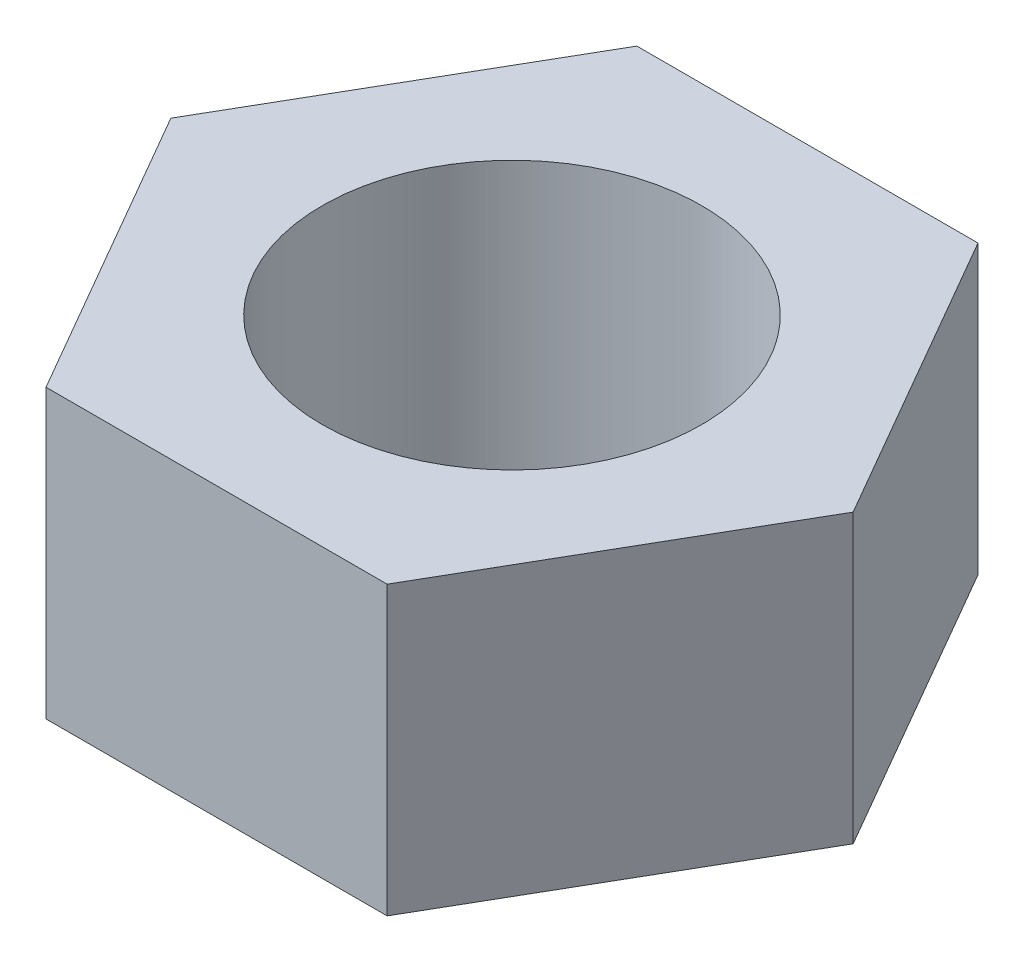
SolidWorks part; units mm, degrees
ref_plane "Front Plane" through (0, 0, 0) normal (0, 0, 1) x (1, 0, 0)
ref_plane "Top Plane" through (0, 0, 0) normal (0, 1, 0) x (1, 0, 0)
ref_plane "Right Plane" through (0, 0, 0) normal (1, 0, 0) x (0, 0, -1)
sketch "Sketch1" plane through (0, 0, 0) normal (0, 1, 0) x (1, 0, 0)
  line L1 (3.1466, -5.45) -> (6.2931, 0)
  line L2 (6.2931, 0) -> (3.1466, 5.45)
  line L3 (3.1466, 5.45) -> (-3.1466, 5.45)
  line L4 (-3.1466, 5.45) -> (-6.2931, 0)
  line L5 (-6.2931, 0) -> (-3.1466, -5.45)
  line L6 (-3.1466, -5.45) -> (3.1466, -5.45)
  circle A0 centre (0, 0) radius 5.45 construction
  circle A1 centre (0, 0) radius 3.5
  dimension "D2" = 7
  dimension "D1" = 10.9
extrude "Boss-Extrude1" add sketch "Sketch1" along normal blind 5.3
